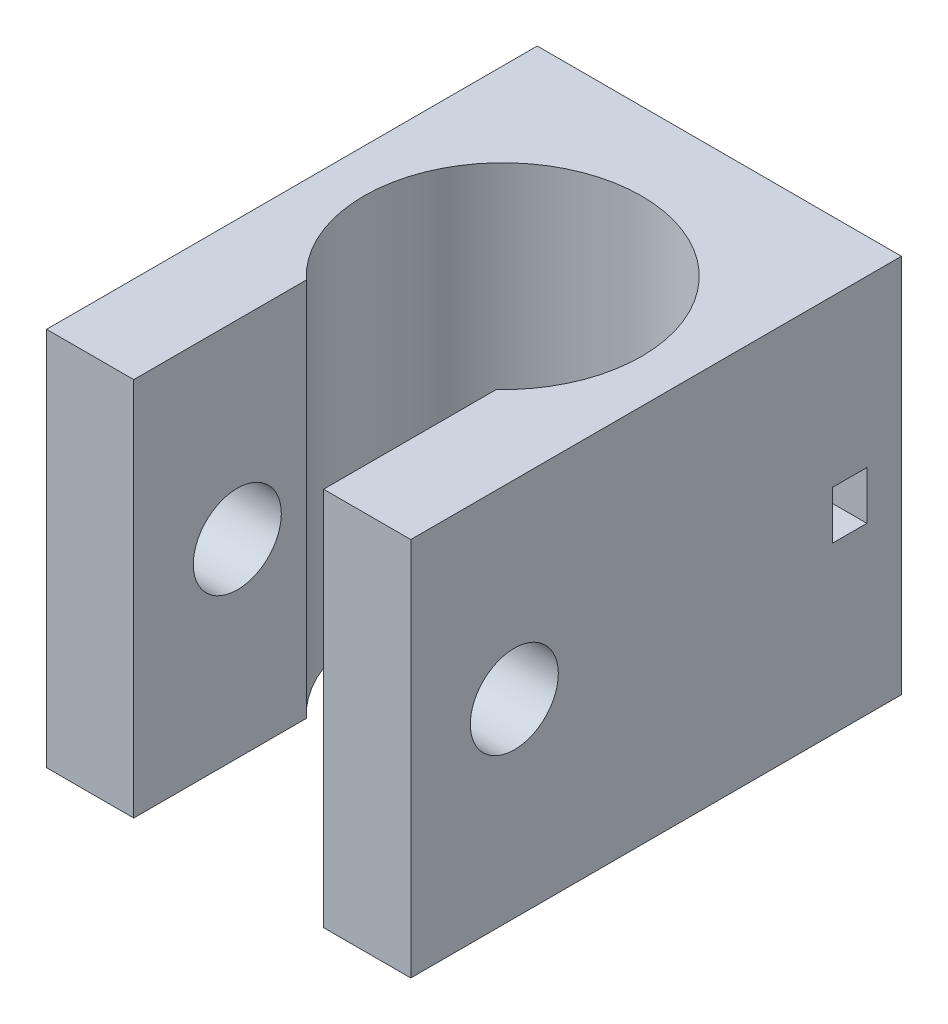
SolidWorks part; units mm, degrees
ref_plane "Front Plane" through (0, 0, 0) normal (0, 0, 1) x (1, 0, 0)
ref_plane "Top Plane" through (0, 0, 0) normal (0, 1, 0) x (1, 0, 0)
ref_plane "Right Plane" through (0, 0, 0) normal (1, 0, 0) x (0, 0, -1)
sketch "Sketch1" plane through (0, 0, 0) normal (0, 1, 0) x (1, 0, 0)
  line L0 (-5.5, -15) -> (-10.55, -15)
  line L1 (-10.55, -15) -> (-10.55, 13.4281)
  line L2 (-10.55, 13.4281) -> (10.55, 13.4281)
  line L3 (10.55, 13.4281) -> (10.55, -15)
  line L4 (10.55, -15) -> (5.5, -15)
  line L5 (5.5, -15) -> (5.5, -5)
  line L6 (-5.5, -15) -> (-5.5, -5)
  line L7 (-44.2539, 0) -> (44.2539, 0) construction
  line L8 (0, -44.7868) -> (0, 44.7868) construction
  arc A0 (-5.5, -5) -> (5.5, -5) centre (0, 0.8781) cw
  dimension "D1" = 8.05
  dimension "D2" = 11
  dimension "D3" = 10
  dimension "D4" = 10
  dimension "D5" = 21.1
  dimension "D6" = 12.55
  dimension "D7" = 15
  dimension "D8" = 10.55
extrude "Boss-Extrude1" add sketch "Sketch1" along normal mid plane 22
sketch "Sketch2" plane through (10.55, 0, 0) normal (1, 0, 0) x (0, 0, -1)
  line L0 (55, 0) -> (-55, 0) construction
  line L1 (-15, 11) -> (-15, -11) construction
  circle A0 centre (-9, 0) radius 2.55
  dimension "D1" = 6
  dimension "D2" = 5.1
extrude "Cut-Extrude1" cut sketch "Sketch2" against normal up to surface (21.1 mm away) up to face at (-10.55, 0, 0.7859)
sketch "Sketch4" plane through (10.55, 0, 0) normal (1, 0, 0) x (0, 0, -1)
  line L1 (9.4281, 1.4) -> (11.4281, 1.4)
  line L2 (9.4281, 1.4) -> (9.4281, -1.4)
  line L3 (9.4281, -1.4) -> (11.4281, -1.4)
  line L4 (11.4281, 1.4) -> (11.4281, -1.4)
  line L5 (-15, 11) -> (13.4281, 11) construction
  line L7 (13.4281, 11) -> (13.4281, -11) construction
  point P6 (10.4281, 1.4)
  dimension "D1" = 2
  dimension "D2" = 2.8
  dimension "D3" = 9.6
  dimension "D4" = 2
extrude "Cut-Extrude3" cut sketch "Sketch4" against normal up to surface (21.1 mm away) up to face at (-10.55, 0, 6.45)
sketch "Sketch5" plane through (0, 0, -13.4281) normal (0, 0, -1) x (-1, 0, 0)
  line L0 (10.55, 11) -> (10.55, -11) construction
  line L1 (-2.4, 8.55) -> (2.5, 8.55)
  line L2 (-2.4, 8.55) -> (-2.4, 3.65)
  line L3 (-2.4, 3.65) -> (2.5, 3.65)
  line L4 (2.5, 8.55) -> (2.5, 3.65)
  line L5 (2.5, -3.65) -> (-2.4, -3.65)
  line L6 (2.5, -3.65) -> (2.5, -8.55)
  line L7 (2.5, -8.55) -> (-2.4, -8.55)
  line L8 (-2.4, -3.65) -> (-2.4, -8.55)
  line L10 (-10.55, 11) -> (10.55, 11) construction
  line L11 (-10.55, -11) -> (10.55, -11) construction
  dimension "D1" = 4.9
  dimension "D5" = 8.05
  dimension "D6" = 8.05
  dimension "D7" = 2.45
  dimension "D8" = 2.45
extrude "Boss-Extrude2" add sketch "Sketch5" along normal blind 2
equation "\"Width\"=21.1"
equation "\"D5@Sketch1\"=\"Width\""
equation "\"D8@Sketch1\"=\"Width\"/2"
equation "\"D6@Sketch1\"=\"Width\"/2+2"
